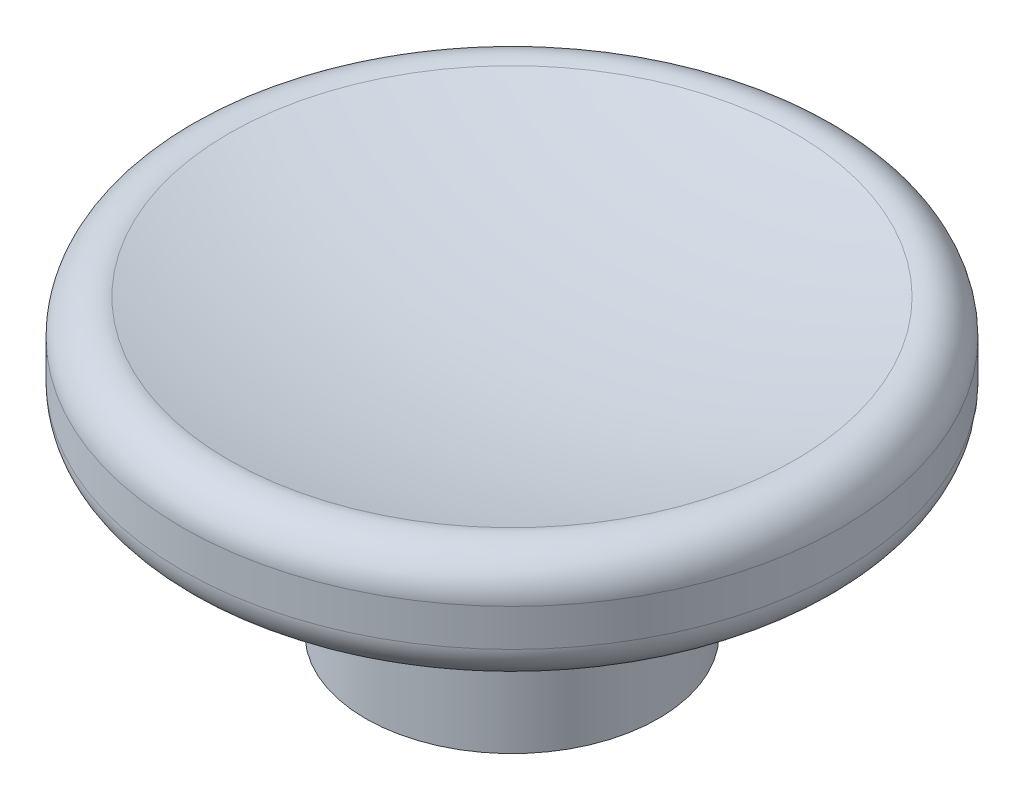
SolidWorks part; units mm, degrees
material "ABS"
ref_plane "前视基准面" through (0, 0, 0) normal (0, 0, 1) x (1, 0, 0)
ref_plane "上视基准面" through (0, 0, 0) normal (0, 1, 0) x (1, 0, 0)
ref_plane "右视基准面" through (0, 0, 0) normal (1, 0, 0) x (0, 0, -1)
other "Configuration Table"
sketch "草图1" plane through (0, 0, 0) normal (0, 1, 0) x (1, 0, 0)
  line L1 (-0.9278, -0.95) -> (0.9278, -0.95)
  line L2 (-0.9278, -0.95) -> (-0.9278, 0.95)
  line L3 (-0.9278, 0.95) -> (0.9278, 0.95)
  line L4 (0.9278, -0.95) -> (0.9278, 0.95)
  line L5 (0, 0.95) -> (0, -0.95) construction
  line L6 (-0.9278, 0) -> (0.9278, 0) construction
  circle A0 centre (0, 0) radius 2
extrude "凸台-拉伸1" add sketch "草图1" along normal blind 2.5
sketch "草图2" plane through (0, 2.5, 0) normal (0, 1, 0) x (1, 0, 0)
  circle A0 centre (0, 0) radius 4.5
extrude "凸台-拉伸2" add sketch "草图2" along normal blind 2
sketch "草图3" plane through (0, 0, 0) normal (0, 0, 1) x (1, 0, 0)
  line L0 (0, 3.4542) -> (0, 31.8542) construction
  line L4 (4.5, 4.5) -> (-4.5, 4.5) construction
  line L5 (-5.3485, 4.5) -> (0, 4.5)
  line L6 (0, 4.5) -> (0, 3.4542)
  arc A1 (0, 31.8542) -> (0, 3.4542) centre (0, 17.6542) ccw construction
  arc A2 (-5.3485, 4.5) -> (0, 3.4542) centre (0, 17.6542) ccw
revolve "切除-旋转6" cut sketch "草图3" angle 360 about L6
fillet "圆角2" radius 0.5 3 edges at (0, 2.5, 2) (0, 2.5, 4.5) (0, 4.1861, 4.5)
sketch "草图4" plane through (0, 2.5, 0) normal (0, -1, 0) x (1, 0, 0)
  line L1 (0.9278, -0.95) -> (-0.9278, -0.95)
  line L2 (0.9278, -0.95) -> (0.9278, 0.95)
  line L3 (0.9278, 0.95) -> (-0.9278, 0.95)
  line L4 (-0.9278, -0.95) -> (-0.9278, 0.95)
  line L5 (0, 0.95) -> (0, -0.95) construction
  line L6 (0.9278, 0) -> (-0.9278, 0) construction
  point P0 (0, 0)
extrude "凸台-拉伸3" add sketch "草图4" along normal blind 0.5
